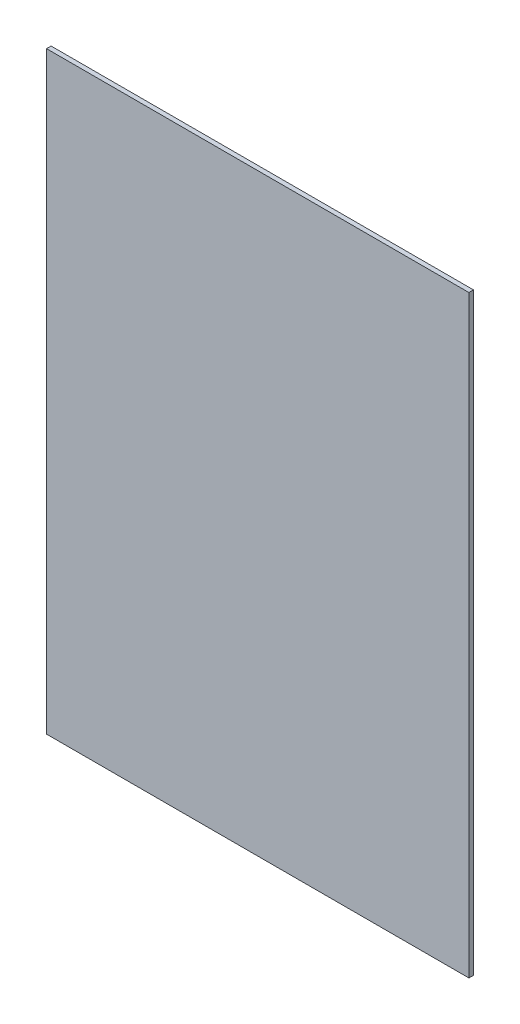
SolidWorks part; units mm, degrees
ref_plane "Ön Düzlem" through (0, 0, 0) normal (0, 0, 1) x (1, 0, 0)
ref_plane "Üst Düzlem" through (0, 0, 0) normal (0, 1, 0) x (1, 0, 0)
ref_plane "Sağ Düzlem" through (0, 0, 0) normal (1, 0, 0) x (0, 0, -1)
sketch "Sketch1" plane through (0, 0, 0) normal (0, 0, 1) x (1, 0, 0)
  line L1 (-185, 260) -> (185, 260)
  line L2 (-185, 260) -> (-185, -260)
  line L3 (-185, -260) -> (185, -260)
  line L4 (185, 260) -> (185, -260)
  line L5 (-185, 260) -> (185, -260) construction
  line L6 (-185, -260) -> (185, 260) construction
  point P0 (0, 0)
  dimension "D1" = 370
  dimension "D2" = 520
extrude "Boss-Extrude1" add sketch "Sketch1" along normal blind 4
